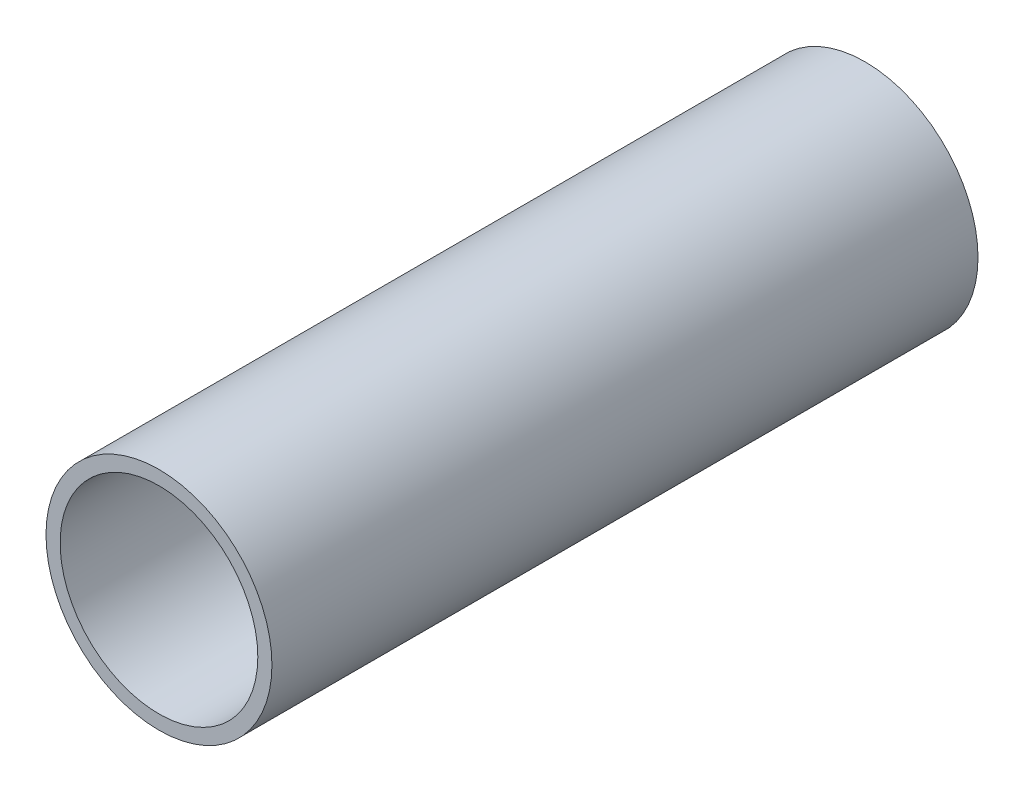
SolidWorks part; units mm, degrees
ref_plane "Front Plane" through (0, 0, 0) normal (0, 0, 1) x (1, 0, 0)
ref_plane "Top Plane" through (0, 0, 0) normal (0, 1, 0) x (1, 0, 0)
ref_plane "Right Plane" through (0, 0, 0) normal (1, 0, 0) x (0, 0, -1)
sketch "Sketch2" plane through (0, 0, 0) normal (0, 0, 1) x (1, 0, 0)
  circle A0 centre (0, 0) radius 40
  circle A1 centre (0, 0) radius 35
  point P3 (0, 0)
  dimension "D1" = 80
  dimension "D2" = 5
extrude "Boss-Extrude1" add sketch "Sketch2" along normal blind 250
